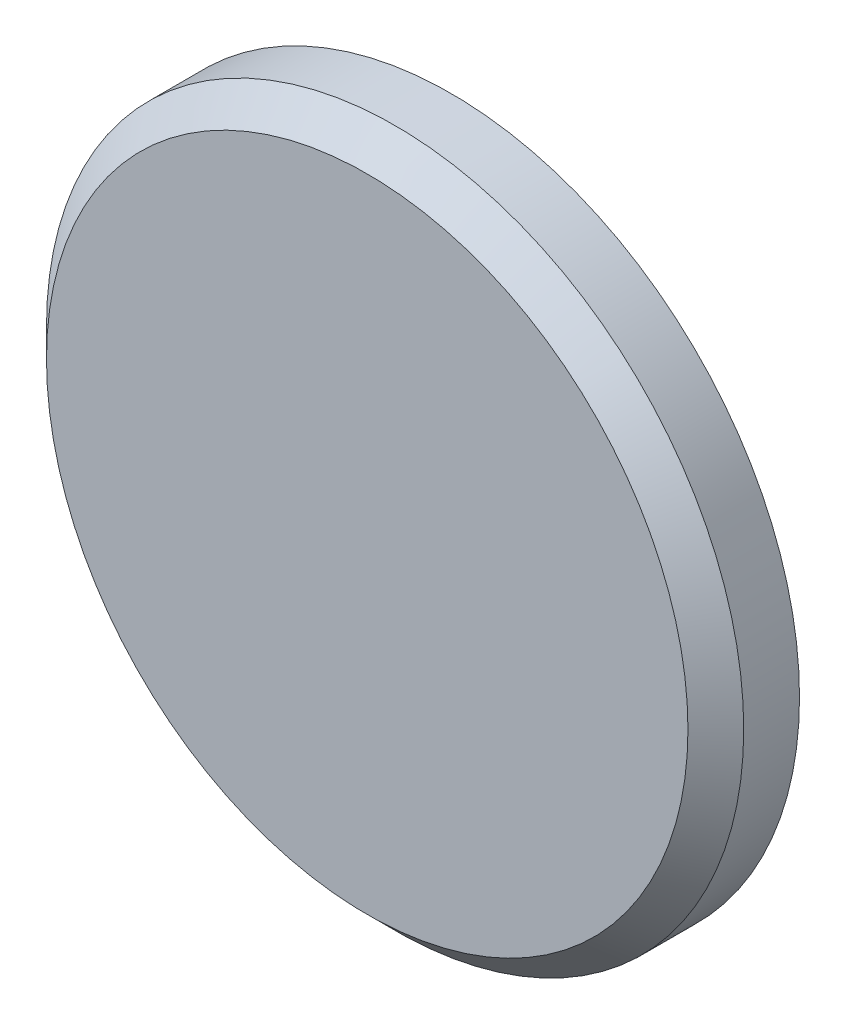
SolidWorks part; units mm, degrees
ref_plane "Plano frontal" through (0, 0, 0) normal (0, 0, 1) x (1, 0, 0)
ref_plane "Plano superior" through (0, 0, 0) normal (0, 1, 0) x (1, 0, 0)
ref_plane "Plano direito" through (0, 0, 0) normal (1, 0, 0) x (0, 0, -1)
sketch "Esboço1" plane through (0, 0, 0) normal (0, 0, 1) x (1, 0, 0)
  circle A0 centre (132.4242, 100) radius 12.5
  ellipse E0 centre (132.4242, 100) end of major axis (128.1579, 100) minor radius 4.25 construction
  dimension "D1" = 25
extrude "Ressalto-extrusão1" add sketch "Esboço1" along normal blind 3
chamfer "Chanfro1" distance 1 angle 45 1 edges at (144.9242, 100, 3)
